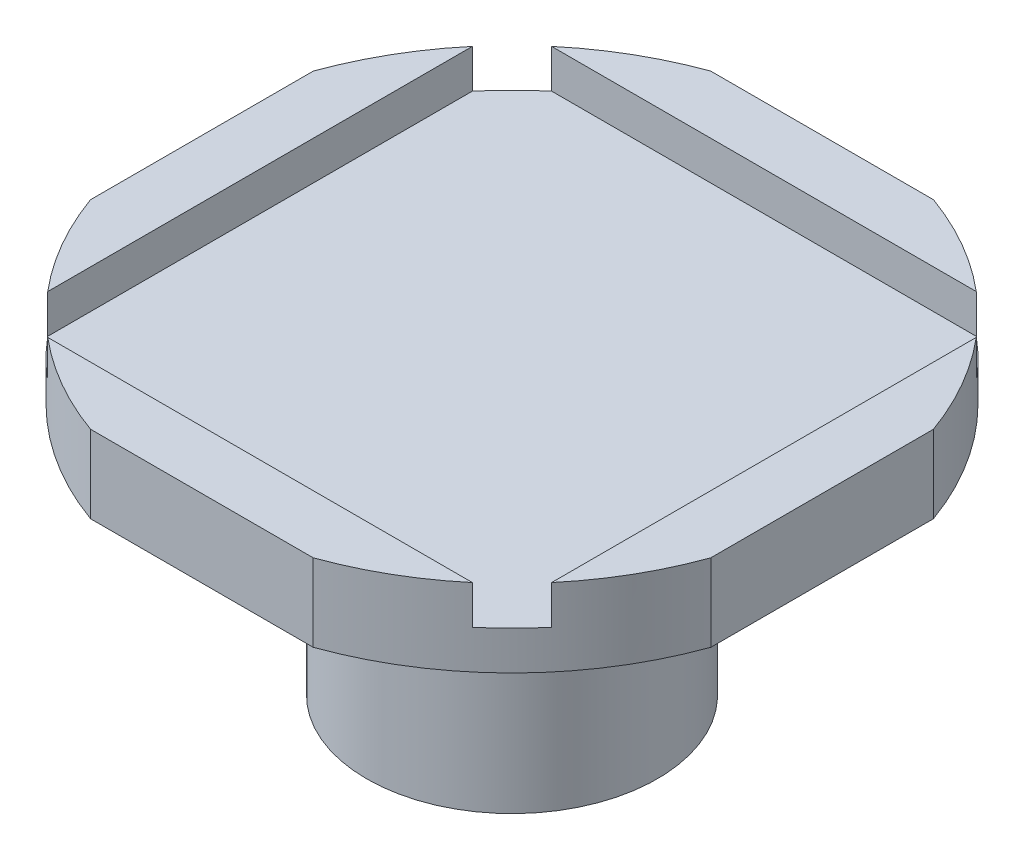
SolidWorks part; units mm, degrees
ref_plane "Plan de face" through (0, 0, 0) normal (0, 0, 1) x (1, 0, 0)
ref_plane "Plan de dessus" through (0, 0, 0) normal (0, 1, 0) x (1, 0, 0)
ref_plane "Plan de droite" through (0, 0, 0) normal (1, 0, 0) x (0, 0, -1)
sketch "Esquisse1" plane through (0, 0, 0) normal (0, 1, 0) x (1, 0, 0)
  circle A0 centre (0, 0) radius 7.5
  dimension "D1" = 15
extrude "Boss.-Extru.1" add sketch "Esquisse1" against normal blind 12
sketch "Esquisse2" plane through (0, 0, 0) normal (0, 1, 0) x (1, 0, 0)
  circle A0 centre (0, 0) radius 8.5
  dimension "D1" = 17
extrude "Boss.-Extru.2" add sketch "Esquisse2" along normal blind 1
sketch "Esquisse3" plane through (0, 1, 0) normal (0, 1, 0) x (1, 0, 0)
  line L1 (-13, -13) -> (13, -13)
  line L2 (-13, -13) -> (-13, 13)
  line L3 (-13, 13) -> (13, 13)
  line L4 (13, -13) -> (13, 13)
  line L5 (-13, -13) -> (13, 13) construction
  line L6 (-13, 13) -> (13, -13) construction
  line L7 (-16, -16) -> (16, -16)
  line L8 (-16, -16) -> (-16, 16)
  line L9 (-16, 16) -> (16, 16)
  line L10 (16, -16) -> (16, 16)
  line L11 (-16, -16) -> (16, 16) construction
  line L12 (-16, 16) -> (16, -16) construction
  point P0 (0, 0)
  point P6 (0, 0)
  circle M7 centre (0, 0) radius 8.5
  dimension "D1" = 26
  dimension "D2" = 26
  dimension "D3" = 3
  dimension "D4" = 3
extrude "Boss.-Extru.3" add sketch "Esquisse3" along normal blind 2 separate body contours L1 L4 L3 L2 M7 | M7 | L7 L10 L9 L8 L4 L1 L2 L3
sketch "Esquisse4" plane through (0, 3, 0) normal (0, 1, 0) x (1, 0, 0)
  line L1 (-13, -13) -> (13, -13)
  line L2 (-13, -13) -> (-13, 13)
  line L3 (-13, 13) -> (13, 13)
  line L4 (13, -13) -> (13, 13)
  line L5 (-13, -13) -> (13, 13) construction
  line L6 (-13, 13) -> (13, -13) construction
  line L7 (-16, -16) -> (16, -16)
  line L8 (-16, -16) -> (-16, 16)
  line L9 (-16, 16) -> (16, 16)
  line L10 (16, -16) -> (16, 16)
  line L11 (-16, -16) -> (16, 16) construction
  line L12 (-16, 16) -> (16, -16) construction
  point P0 (0, 0)
  point P7 (0, 0)
extrude "Boss.-Extru.4" add sketch "Esquisse4" along normal blind 2
sketch "Esquisse6" plane through (0, 5, 0) normal (0, 1, 0) x (1, 0, 0)
  circle A0 centre (0, 0) radius 17
  circle A1 centre (0, 0) radius 32.5234
  dimension "D1" = 34
extrude "Enlèv. mat.-Extru.1" cut sketch "Esquisse6" against normal through all
